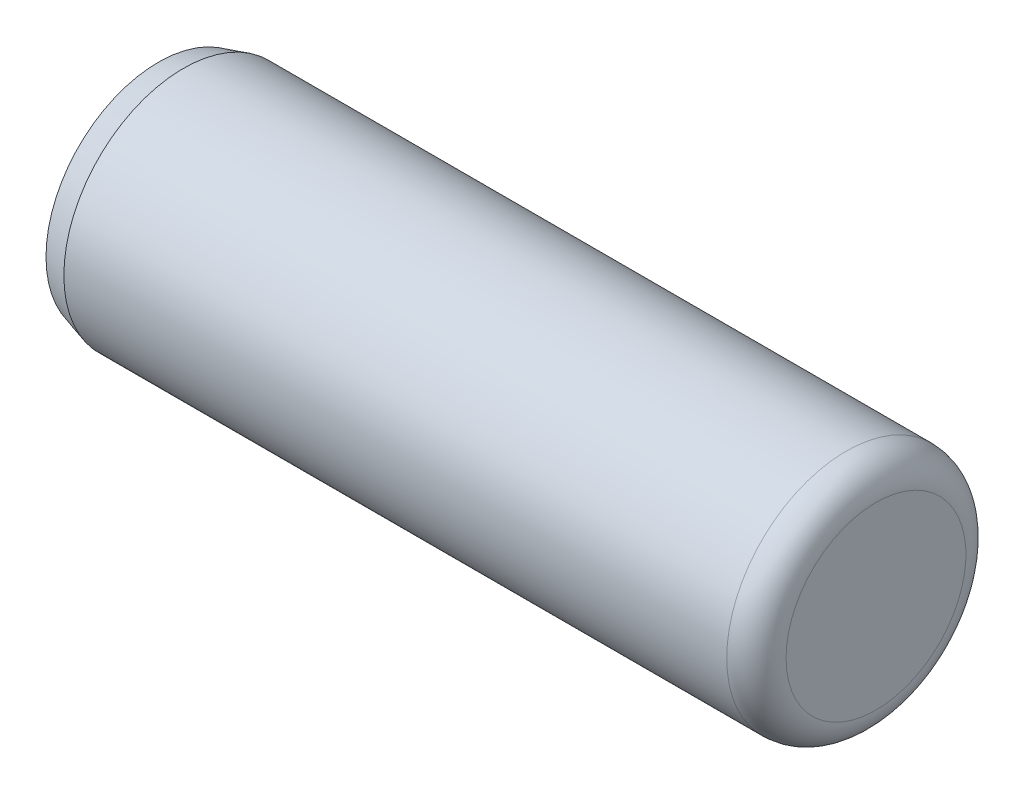
SolidWorks part; units mm, degrees
ref_plane "Front" through (0, 0, 0) normal (0, 0, 1) x (1, 0, 0)
ref_plane "Top" through (0, 0, 0) normal (0, 1, 0) x (1, 0, 0)
ref_plane "Right" through (0, 0, 0) normal (1, 0, 0) x (0, 0, -1)
sketch "Sketch1" plane through (0, 0, 0) normal (1, 0, 0) x (0, 0, -1)
  circle A0 centre (0, 0) radius 3.175 construction
  point P3 (0, 3.175)
  dimension "Diameter" = 6.35
sketch "Sketch2" plane through (0, 0, 0) normal (0, 0, 1) x (1, 0, 0)
  line L0 (-9.525, 0) -> (9.525, 0) construction
  line L1 (9.525, 2.3876) -> (9.525, -0.6481) construction
  line L2 (-9.525, 2.9845) -> (-9.525, -2.9845) construction
  line L3 (-9.525, 2.9845) -> (-9.525, 3.175) construction
  line L4 (-9.525, -2.9845) -> (-9.525, -3.175) construction
  line L5 (-9.525, 2.9845) -> (-8.8606, 3.175) construction
  line L6 (-8.8606, 3.175) -> (8.7376, 3.175) construction
  arc A0 (8.7376, 3.175) -> (9.525, 2.3876) centre (8.7376, 2.3876) cw construction
  point P6 (-3.175, 0)
  point P8 (3.175, 0)
  point P23 (7.4168, 3.175)
  dimension "Crown Radius" = 0.7874
  dimension "Length" = 19.05
  dimension "D1" = 6.35
  dimension "D2" = 6.35
  dimension "Point Diameter" = 5.969
  dimension "D3" = 16
  dimension "Crown Height" = 2.1082
sketch "Sketch3" plane through (0, 0, 0) normal (0, 0, 1) x (1, 0, 0)
  line L0 (9.525, 2.3876) -> (9.525, -0.6481) construction
  line L1 (-8.8606, 3.175) -> (8.7376, 3.175) construction
  line L2 (-9.525, 2.9845) -> (-8.8606, 3.175) construction
  line L3 (-9.525, 2.9845) -> (-9.525, -2.9845) construction
  line L4 (-9.525, 0) -> (9.525, 0) construction
  line L5 (9.525, 2.3876) -> (9.525, 0)
  line L6 (-8.8606, 3.175) -> (8.7376, 3.175)
  line L7 (-9.525, 2.9845) -> (-8.8606, 3.175)
  line L8 (-9.525, 2.9845) -> (-9.525, 0)
  line L9 (-9.525, 0) -> (9.525, 0)
  arc A0 (9.525, 2.3876) -> (8.7376, 3.175) centre (8.7376, 2.3876) ccw construction
  arc A1 (9.525, 2.3876) -> (8.7376, 3.175) centre (8.7376, 2.3876) ccw
revolve "Revolve1" add sketch "Sketch3" angle 360 about L0
equation "\"D1@Sketch2\" = \"Diameter@Sketch1\""
equation "\"D2@Sketch2\" = \"Diameter@Sketch1\""
